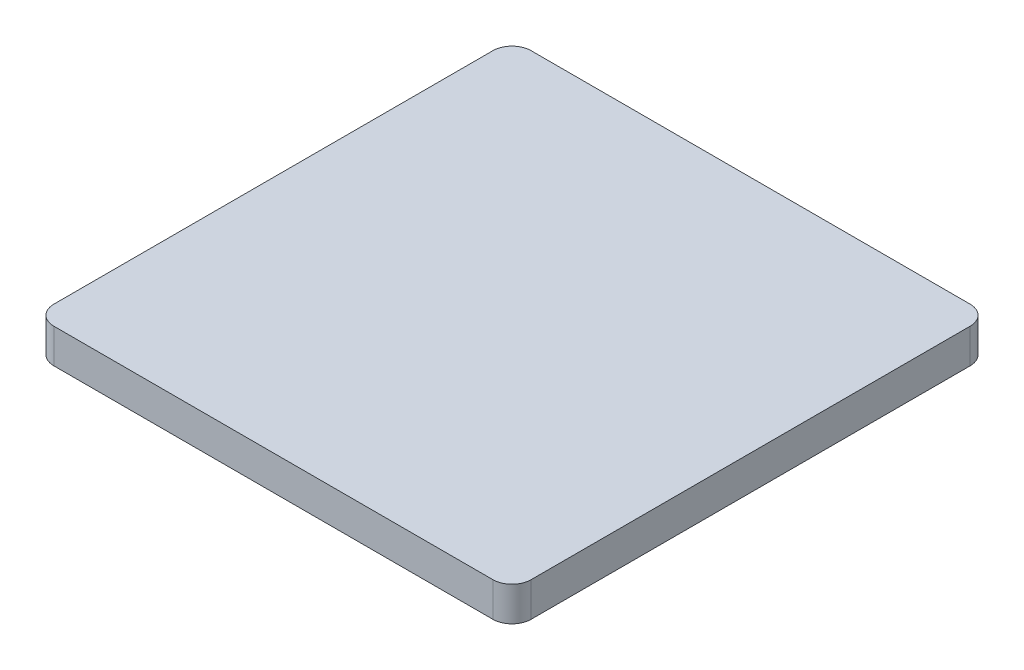
SolidWorks part; units mm, degrees
ref_plane "前视基准面" through (0, 0, 0) normal (0, 0, 1) x (1, 0, 0)
ref_plane "上视基准面" through (0, 0, 0) normal (0, 1, 0) x (1, 0, 0)
ref_plane "右视基准面" through (0, 0, 0) normal (1, 0, 0) x (0, 0, -1)
other "Configuration Table"
sketch "草图1" plane through (0, 0, 0) normal (0, 1, 0) x (1, 0, 0)
  line L1 (-125, -125) -> (125, -125)
  line L2 (-125, -125) -> (-125, 125)
  line L3 (-125, 125) -> (125, 125)
  line L4 (125, -125) -> (125, 125)
  point P4 (-125, 0)
  point P6 (0, 125)
  dimension "D1" = 250
  dimension "D2" = 250
extrude "凸台-拉伸1" add sketch "草图1" along normal blind 18
fillet "圆角1" radius 10 4 edges at (-125, 9, -125) (125, 9, -125) (125, 9, 125) (-125, 9, 125)
